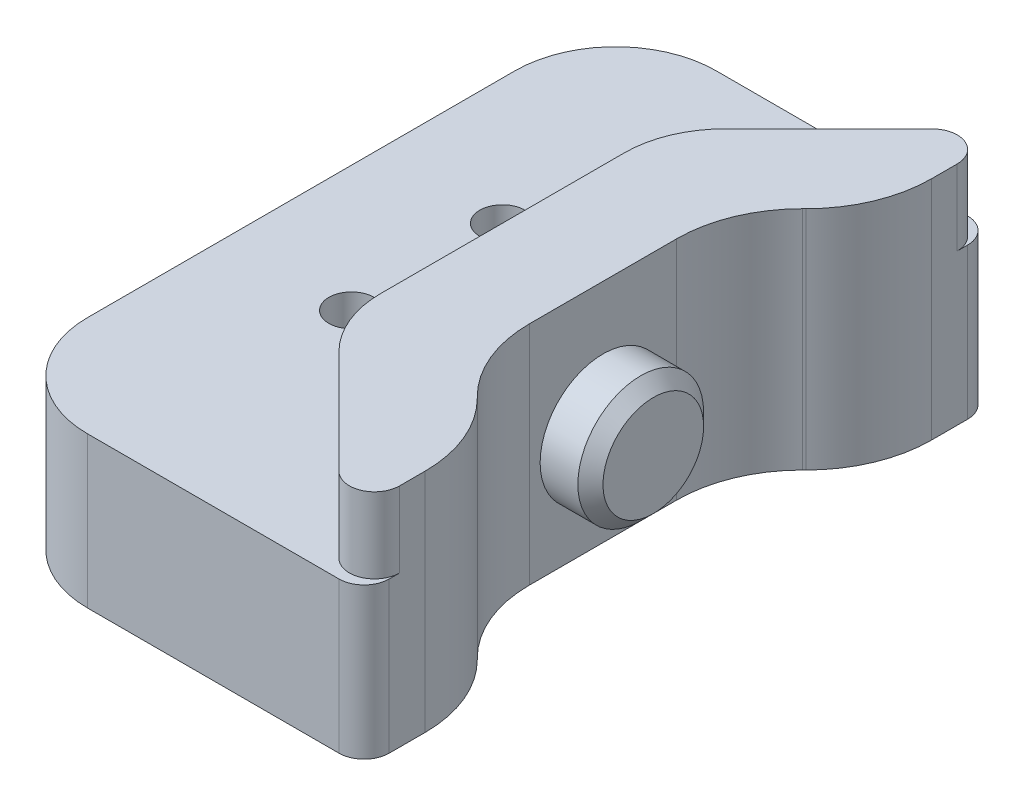
SolidWorks part; units mm, degrees
material "PLA"
ref_plane "前视基准面" through (0, 0, 0) normal (0, 0, 1) x (1, 0, 0)
ref_plane "上视基准面" through (0, 0, 0) normal (0, 1, 0) x (1, 0, 0)
ref_plane "右视基准面" through (0, 0, 0) normal (1, 0, 0) x (0, 0, -1)
sketch "草图1" plane through (0, 0, 0) normal (0, 1, 0) x (1, 0, 0)
  line L0 (0, 12.5) -> (0, -12.5)
  line L1 (0, -12.5) -> (15, -12.5)
  line L2 (15, -12.5) -> (15, -8)
  line L3 (15, 12.5) -> (0, 12.5)
  line L4 (0, 0) -> (15, 0) construction
  line L5 (15, 8) -> (12, 5)
  line L6 (12, 5) -> (12, -5)
  line L7 (12, -5) -> (15, -8)
  line L8 (15, 8) -> (15, 12.5)
  circle A0 centre (5, 3) radius 0.9
  circle A1 centre (5, -3) radius 0.9
  dimension "D3" = 5
  dimension "D4" = 6
  dimension "D5" = 1.8
  dimension "D6" = 3
  dimension "D7" = 10
  dimension "D1" = 25
  dimension "D2" = 15
extrude "凸台-拉伸1" add sketch "草图1" along normal blind 6
sketch "草图2" plane through (0, 6, 0) normal (0, 1, 0) x (1, 0, 0)
  line L0 (13.2929, 11.7929) -> (8, 6.5)
  line L1 (15, -8) -> (12, -5) construction
  line L2 (8, 6.5) -> (8, -6.5)
  line L3 (8, -6.5) -> (13.2929, -11.7929)
  line L4 (12, -5) -> (12, 5) construction
  line L5 (0, 0) -> (8, 0) construction
  line L6 (12, 5) -> (15, 8) construction
  line L7 (15, -8) -> (12, -5)
  line L8 (15, 11.0858) -> (15, 8)
  line L9 (12, -5) -> (12, 5)
  line L10 (15, -12.5) -> (15, -8) construction
  line L11 (12, 5) -> (15, 8)
  line L12 (15, -8) -> (15, -11.0858)
  circle A0 centre (5, 3) radius 0.9 construction
  arc A1 (13.2929, 11.7929) -> (15, 11.0858) centre (14, 11.0858) cw
  arc A2 (13.2929, -11.7929) -> (15, -11.0858) centre (14, -11.0858) ccw
  dimension "D2" = 3
  dimension "D3" = 1
  dimension "D1" = 13
extrude "凸台-拉伸2" add sketch "草图2" along normal blind 3
fillet "圆角2" radius 4 4 edges at (8, 7.5, -6.5) (8, 7.5, 6.5) (0, 3, -12.5) (0, 3, 12.5)
fillet "圆角3" radius 1 2 edges at (15, 3, 12.5) (15, 3, -12.5)
sketch "草图3" plane through (12, 0, 0) normal (1, 0, 0) x (0, 0, -1)
  line L0 (-11.5, 0) -> (-8, 0) construction
  circle A1 centre (0, 4) radius 2.5
  dimension "D1" = 5
  dimension "D2" = 4
extrude "凸台-拉伸3" add sketch "草图3" along normal blind 2
fillet "圆角4" radius 5 4 edges at (15, 4.5, 8) (12, 4.5, 5) (15, 4.5, -8) (12, 4.5, -5)
chamfer "倒角1" distance 0.5 angle 45 1 edges at (14, 4, -2.5)
